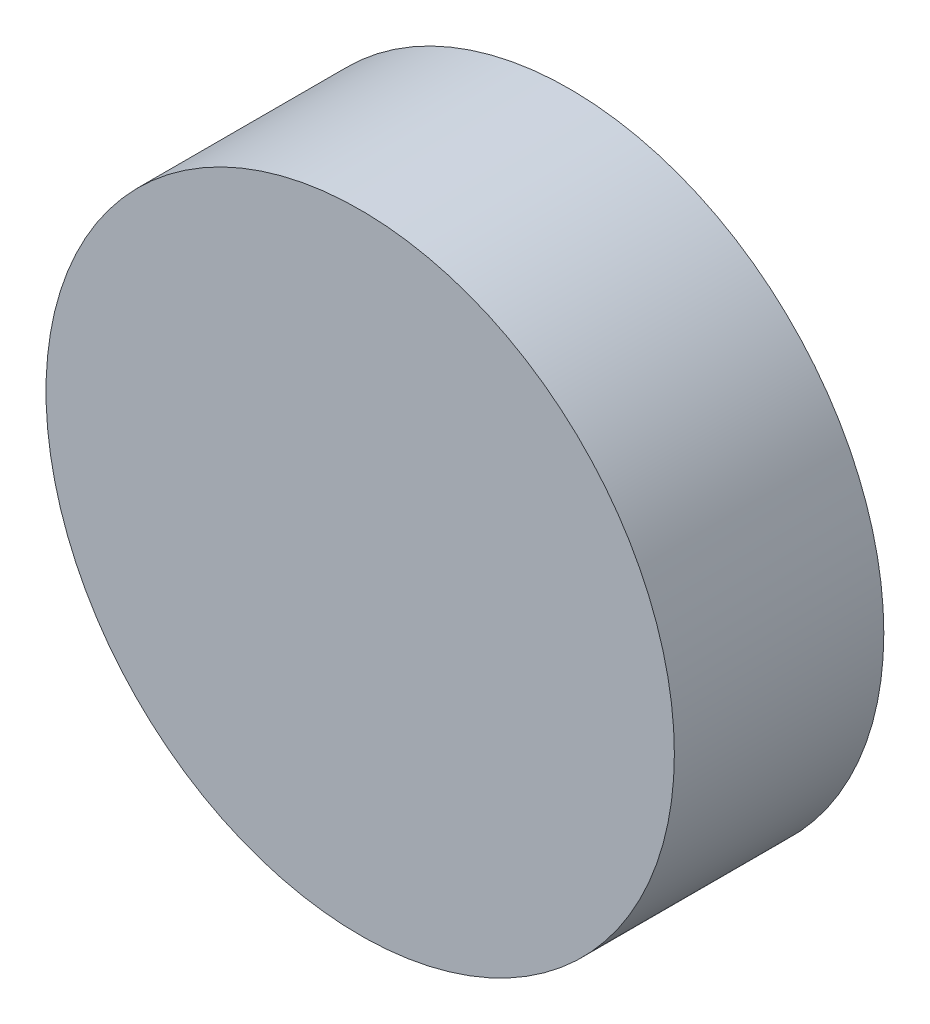
SolidWorks part; units mm, degrees
ref_plane "Front Plane" through (0, 0, 0) normal (0, 0, 1) x (1, 0, 0)
ref_plane "Top Plane" through (0, 0, 0) normal (0, 1, 0) x (1, 0, 0)
ref_plane "Right Plane" through (0, 0, 0) normal (1, 0, 0) x (0, 0, -1)
sketch "Sketch1" plane through (0, 0, 0) normal (0, 0, 1) x (1, 0, 0)
  circle A0 centre (0, 0) radius 3.75
  dimension "D1" = 7.5
extrude "Boss-Extrude1" add sketch "Sketch1" along normal blind 2.5
